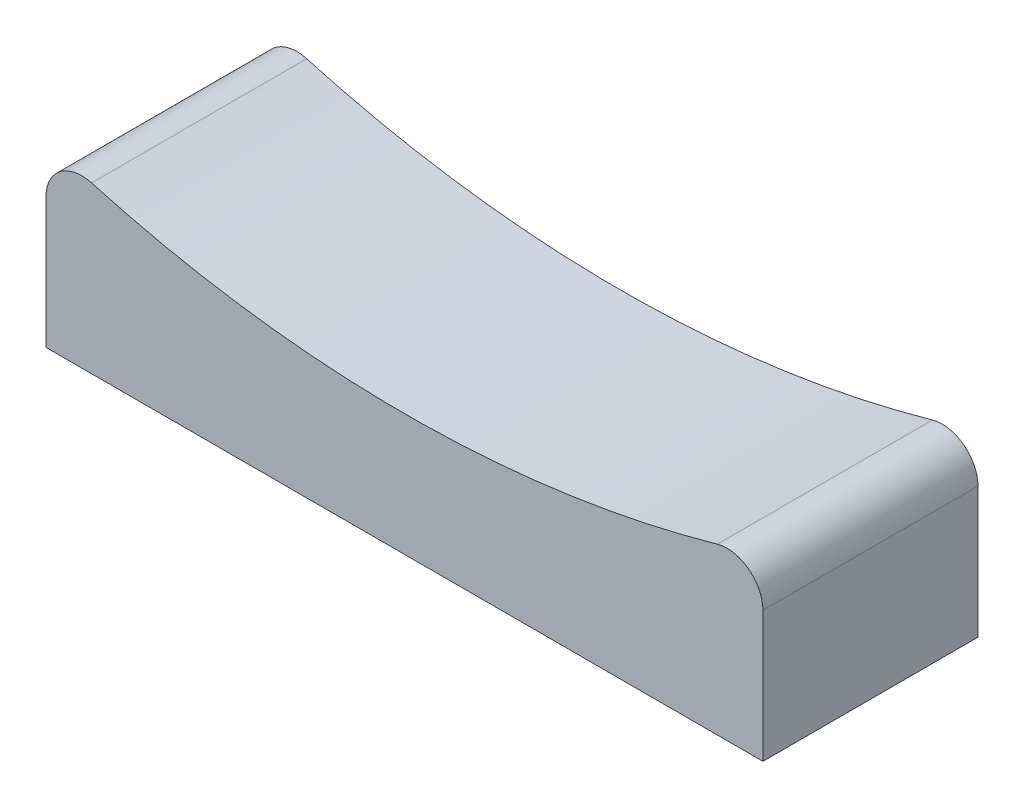
SolidWorks part; units mm, degrees
ref_plane "Front Plane" through (0, 0, 0) normal (0, 0, 1) x (1, 0, 0)
ref_plane "Top Plane" through (0, 0, 0) normal (0, 1, 0) x (1, 0, 0)
ref_plane "Right Plane" through (0, 0, 0) normal (1, 0, 0) x (0, 0, -1)
sketch "Sketch1" plane through (0, 0, 0) normal (0, 1, 0) x (1, 0, 0)
  line L1 (-50, 15) -> (50, 15)
  line L2 (-50, 15) -> (-50, -15)
  line L3 (-50, -15) -> (50, -15)
  line L4 (50, 15) -> (50, -15)
  line L5 (-50, 15) -> (50, -15) construction
  line L6 (-50, -15) -> (50, 15) construction
  point P0 (0, 0)
  dimension "D1" = 100
  dimension "D2" = 30
extrude "Boss-Extrude1" add sketch "Sketch1" along normal blind 20
sketch "Sketch2" plane through (0, 0, 15) normal (0, 0, 1) x (1, 0, 0)
  line L1 (-50, 20) -> (50, 20)
  arc A0 (-50, 20) -> (50, 20) centre (0, 172.25) ccw
  point P8 (0, 12)
  dimension "D1" = 8
extrude "Cut-Extrude1" cut sketch "Sketch2" against normal through all
fillet "Fillet1" radius 5 2 edges at (50, 20, 0) (-50, 20, 0)
sketch "Sketch3" plane through (0, 0, 0) normal (0, -1, 0) x (1, 0, 0)
  line L1 (-50, 15) -> (50, 15)
  line L2 (-50, 15) -> (-50, -15)
  line L3 (-50, -15) -> (50, -15)
  line L4 (50, 15) -> (50, -15)
extrude "Boss-Extrude2" add sketch "Sketch3" along normal blind 5
sketch "Sketch4" plane through (0, -5, 0) normal (0, -1, 0) x (1, 0, 0)
  circle A0 centre (0, 0) radius 7.675
  dimension "D1" = 15.35
extrude "Cut-Extrude2" cut sketch "Sketch4" against normal blind 5
chamfer "Chamfer1" distance 1 angle 45 1 edges at (0, -5, -7.675)
